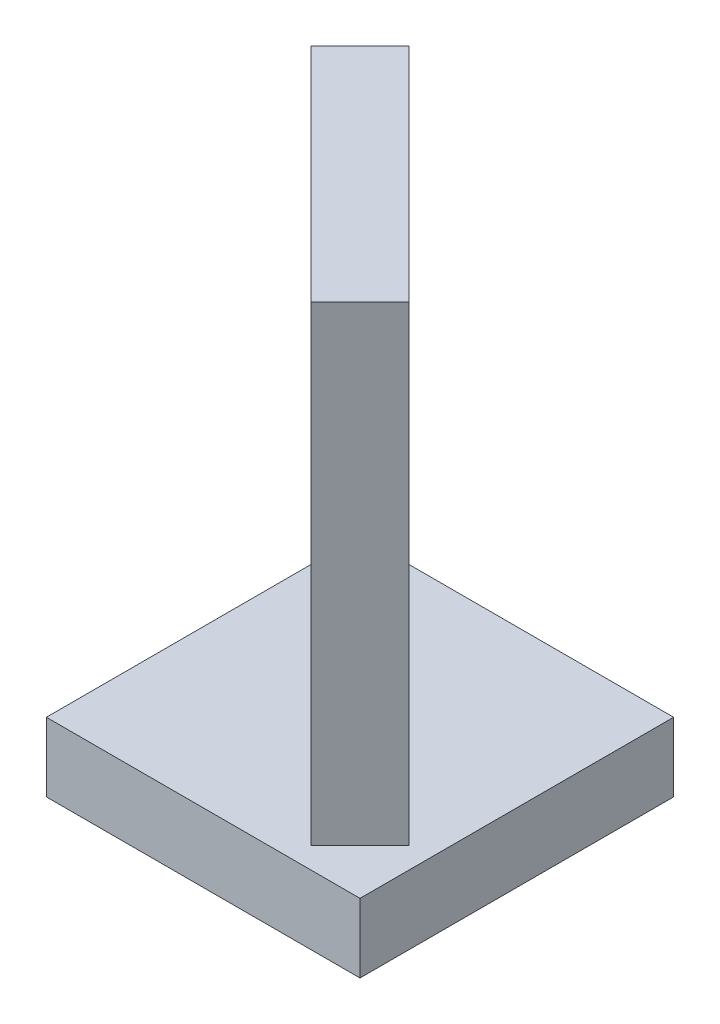
SolidWorks part; units mm, degrees
ref_plane "Front Plane" through (0, 0, 0) normal (0, 0, 1) x (1, 0, 0)
ref_plane "Top Plane" through (0, 0, 0) normal (0, 1, 0) x (1, 0, 0)
ref_plane "Right Plane" through (0, 0, 0) normal (1, 0, 0) x (0, 0, -1)
sketch "Sketch1" plane through (0, 0, 0) normal (0, 1, 0) x (1, 0, 0)
  line L1 (-12.7, -12.7) -> (12.7, -12.7)
  line L2 (-12.7, -12.7) -> (-12.7, 12.7)
  line L3 (-12.7, 12.7) -> (12.7, 12.7)
  line L4 (12.7, -12.7) -> (12.7, 12.7)
  line L5 (-12.7, -12.7) -> (12.7, 12.7) construction
  line L6 (-12.7, 12.7) -> (12.7, -12.7) construction
  point P0 (0, 0)
  dimension "D1" = 25.4
  dimension "D2" = 25.4
extrude "Boss-Extrude1" add sketch "Sketch1" along normal blind 5.588
sketch "Sketch2" plane through (0, 5.588, 0) normal (0, 1, 0) x (1, 0, 0)
  line L0 (-12.7, 12.7) -> (12.7, -12.7) construction
  line L2 (-7.0046, 10.9559) -> (10.9559, -7.0046)
  line L3 (-7.0046, 10.9559) -> (-10.9559, 7.0046)
  line L4 (-10.9559, 7.0046) -> (7.0046, -10.9559)
  line L5 (10.9559, -7.0046) -> (7.0046, -10.9559)
  line L6 (-7.0046, 10.9559) -> (7.0046, -10.9559) construction
  line L7 (-10.9559, 7.0046) -> (10.9559, -7.0046) construction
  point P4 (0, 0)
  point P10 (5.6377, 4.2488)
  point P11 (-10.1019, -1.264)
  point P12 (3.5204, -10.7717)
  point P13 (9.5526, 0.4537)
  point P14 (-2.6316, 10.6804)
  point P15 (-8.9803, 8.9803)
  point P16 (8.9803, -8.9803)
  point P17 (-2.5916, 6.0864)
  point P18 (-1.9524, 8.4433)
  point P19 (-2.4718, 5.5671)
  point P20 (11.3503, 1.0529)
  point P21 (8.1145, -5.1789)
  point P22 (8.8335, -3.0218)
  dimension "D1" = 90
  dimension "D2" = 5.588
  dimension "D3" = 25.4
extrude "Boss-Extrude2" add sketch "Sketch2" along normal blind 38.1
